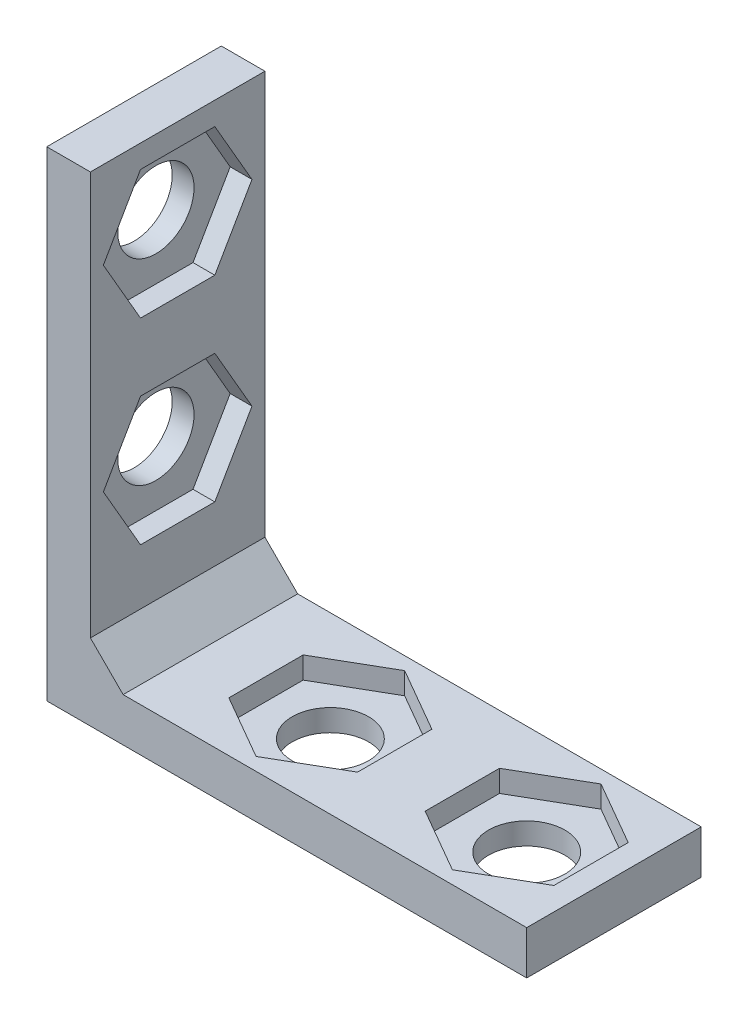
SolidWorks part; units mm, degrees
ref_plane "Piano frontale" through (0, 0, 0) normal (0, 0, 1) x (1, 0, 0)
ref_plane "Piano superiore" through (0, 0, 0) normal (0, 1, 0) x (1, 0, 0)
ref_plane "Piano destro" through (0, 0, 0) normal (1, 0, 0) x (0, 0, -1)
sketch "Schizzo1" plane through (0, 0, 0) normal (0, 0, 1) x (1, 0, 0)
  line L0 (0, 0) -> (0, 22)
  line L1 (0, 22) -> (2, 22)
  line L2 (2, 22) -> (2, 2)
  line L3 (2, 2) -> (22, 2)
  line L4 (22, 2) -> (22, 0)
  line L5 (22, 0) -> (0, 0)
  dimension "D1" = 22
  dimension "D2" = 2
extrude "Estrusione-Estrusione1" add sketch "Schizzo1" along normal blind 8
sketch "Schizzo2" plane through (2, 0, 0) normal (1, 0, 0) x (0, 0, -1)
  line L0 (-8, 22) -> (0, 22) construction
  line L1 (-2.2968, 15.05) -> (-0.5936, 18)
  line L2 (-0.5936, 18) -> (-2.2968, 20.95)
  line L3 (-2.2968, 20.95) -> (-5.7032, 20.95)
  line L4 (-5.7032, 20.95) -> (-7.4064, 18)
  line L5 (-7.4064, 18) -> (-5.7032, 15.05)
  line L6 (-5.7032, 15.05) -> (-2.2968, 15.05)
  line L7 (-2.2968, 6.05) -> (-0.5936, 9)
  line L8 (-0.5936, 9) -> (-2.2968, 11.95)
  line L9 (-2.2968, 11.95) -> (-5.7032, 11.95)
  line L10 (-5.7032, 11.95) -> (-7.4064, 9)
  line L11 (-7.4064, 9) -> (-5.7032, 6.05)
  line L12 (-5.7032, 6.05) -> (-2.2968, 6.05)
  line L13 (-4, 22) -> (-4, 18) construction
  line L14 (-4, 18) -> (-4, 9) construction
  circle A0 centre (-4, 18) radius 2.95 construction
  circle A1 centre (-4, 9) radius 2.95 construction
  dimension "D1" = 5.9
  dimension "D2" = 9
  dimension "D3" = 4
extrude "Taglio-Estrusione1" cut sketch "Schizzo2" against normal blind 1
sketch "Schizzo4" plane through (1, 0, 0) normal (1, 0, 0) x (0, 0, -1)
  line L0 (-4, 20.95) -> (-4, 15.05) construction
  line L1 (-2.2968, 20.95) -> (-5.7032, 20.95) construction
  line L2 (-5.7032, 15.05) -> (-2.2968, 15.05) construction
  line L3 (-4, 11.95) -> (-4, 6.05) construction
  line L4 (-2.2968, 11.95) -> (-5.7032, 11.95) construction
  line L5 (-5.7032, 6.05) -> (-2.2968, 6.05) construction
  circle A0 centre (-4, 18) radius 1.75
  circle A1 centre (-4, 9) radius 1.75
  point P17 (-4, 18)
  dimension "D1" = 3.5
extrude "Taglio-Estrusione2" cut sketch "Schizzo4" against normal through all
sketch "Schizzo5" plane through (0, 2, 0) normal (0, 1, 0) x (1, 0, 0)
  line L0 (22, -4) -> (18, -4) construction
  line L1 (22, -8) -> (22, 0) construction
  line L2 (18, -4) -> (9, -4) construction
  line L6 (15.05, -5.7032) -> (18, -7.4064)
  line L7 (18, -7.4064) -> (20.95, -5.7032)
  line L8 (20.95, -5.7032) -> (20.95, -2.2968)
  line L9 (20.95, -2.2968) -> (18, -0.5936)
  line L10 (18, -0.5936) -> (15.05, -2.2968)
  line L11 (15.05, -2.2968) -> (15.05, -5.7032)
  line L12 (6.05, -5.7032) -> (9, -7.4064)
  line L13 (9, -7.4064) -> (11.95, -5.7032)
  line L14 (11.95, -5.7032) -> (11.95, -2.2968)
  line L15 (11.95, -2.2968) -> (9, -0.5936)
  line L16 (9, -0.5936) -> (6.05, -2.2968)
  line L17 (6.05, -2.2968) -> (6.05, -5.7032)
  circle A0 centre (18, -4) radius 2.95 construction
  circle A1 centre (9, -4) radius 2.95 construction
  dimension "D2" = 5.9
  dimension "D1" = 9
  dimension "D3" = 4
extrude "Taglio-Estrusione3" cut sketch "Schizzo5" against normal blind 1
sketch "Schizzo6" plane through (0, 1, 0) normal (0, 1, 0) x (1, 0, 0)
  line L0 (20.95, -4) -> (15.05, -4) construction
  line L1 (20.95, -5.7032) -> (20.95, -2.2968) construction
  line L2 (15.05, -2.2968) -> (15.05, -5.7032) construction
  line L3 (11.95, -4) -> (6.05, -4) construction
  line L4 (11.95, -5.7032) -> (11.95, -2.2968) construction
  line L5 (6.05, -2.2968) -> (6.05, -5.7032) construction
  circle A0 centre (18, -4) radius 1.75
  circle A1 centre (9, -4) radius 1.75
  dimension "D1" = 3.5
extrude "Taglio-Estrusione4" cut sketch "Schizzo6" against normal through all
chamfer "Smusso1" distance 1.5 angle 45 1 edges at (2, 2, 4)
